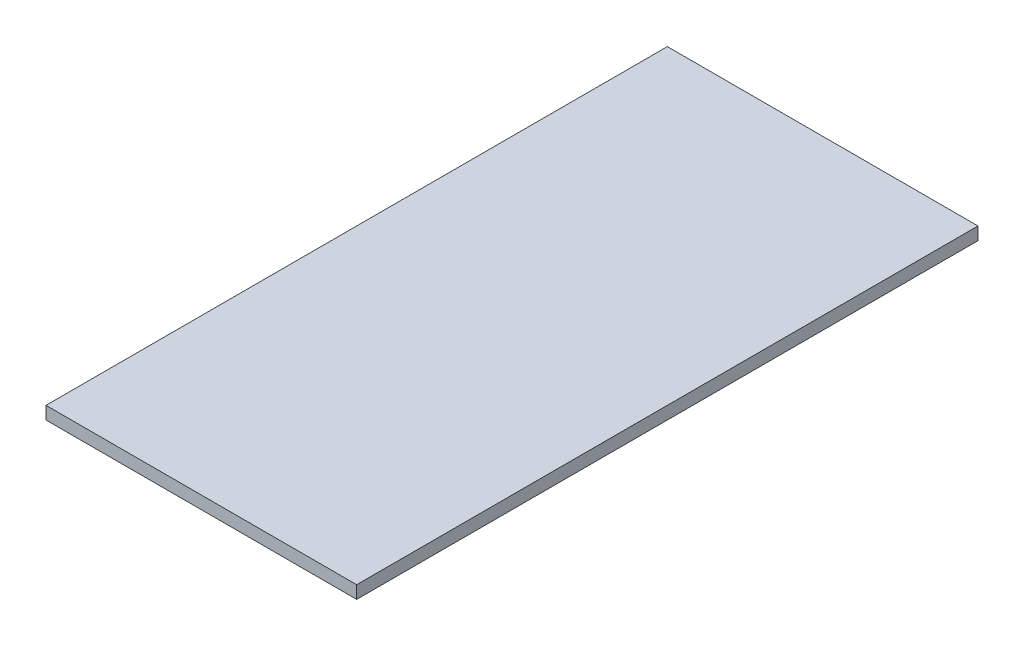
SolidWorks part; units mm, degrees
ref_plane "Front Plane" through (0, 0, 0) normal (0, 0, 1) x (1, 0, 0)
ref_plane "Top Plane" through (0, 0, 0) normal (0, 1, 0) x (1, 0, 0)
ref_plane "Right Plane" through (0, 0, 0) normal (1, 0, 0) x (0, 0, -1)
sketch "Sketch1" plane through (0, 0, 0) normal (0, 1, 0) x (1, 0, 0)
  line L1 (1219.2, -2438.4) -> (-1219.2, -2438.4)
  line L2 (1219.2, -2438.4) -> (1219.2, 2438.4)
  line L3 (1219.2, 2438.4) -> (-1219.2, 2438.4)
  line L4 (-1219.2, -2438.4) -> (-1219.2, 2438.4)
  line L5 (1219.2, -2438.4) -> (-1219.2, 2438.4) construction
  line L6 (1219.2, 2438.4) -> (-1219.2, -2438.4) construction
  point P0 (0, 0)
  dimension "D1" = 4876.8
  dimension "D2" = 2438.4
extrude "Boss-Extrude1" add sketch "Sketch1" along normal blind 100
sketch "Sketch2" plane through (0, 100, 0) normal (0, 1, 0) x (1, 0, 0)
  line L0 (-1219.2, 2438.4) -> (-1219.2, -2438.4) construction
  line L1 (-919.2, -2338.4) -> (-1169.2, -2338.4)
  line L2 (-919.2, -2338.4) -> (-919.2, -2228.4)
  line L3 (-919.2, -2088.4) -> (-1169.2, -2088.4)
  line L4 (-1169.2, -2338.4) -> (-1169.2, -2088.4)
  line L5 (-919.2, -2338.4) -> (-1169.2, -2088.4) construction
  line L6 (-919.2, -2088.4) -> (-1169.2, -2338.4) construction
  line L7 (-1219.2, -2438.4) -> (1219.2, -2438.4) construction
  line L8 (-919.2, -2228.4) -> (-519.2, -2228.4)
  line L9 (-919.2, -2213.4) -> (-874.2776, -2213.4) construction
  line L10 (-919.2, -2198.4) -> (-519.2, -2198.4)
  line L11 (-919.2, -2198.4) -> (-919.2, -2088.4)
  line L12 (518.6973, -2271.9533) -> (948.6973, -2271.9533)
  line L13 (518.6973, -2241.9533) -> (918.6973, -2241.9533)
  line L14 (918.6973, -2241.9533) -> (918.6973, -1841.9533)
  line L15 (948.6973, -2271.9533) -> (948.6973, -1841.9533)
  line L17 (518.6973, -1539.0748) -> (218.6973, -1539.0748)
  line L18 (218.6973, -1539.0748) -> (218.6973, -1567.2032)
  line L19 (218.6973, -1567.2032) -> (518.6973, -1567.2032)
  line L20 (-1019.2, -1938.4) -> (-719.2, -1938.4)
  line L21 (-719.2, -1938.4) -> (-719.2, -1908.4)
  line L22 (-719.2, -1908.4) -> (-989.2, -1908.4)
  line L23 (-989.2, -1908.4) -> (-989.2, -415)
  line L24 (-989.2, -415) -> (-479.8558, -415)
  line L25 (300, -400) -> (-1082.2018, -400) construction
  line L26 (-1019.2, -1938.4) -> (-1019.2, -385)
  line L27 (-1019.2, -385) -> (-479.8558, -385)
  line L28 (300, -400) -> (300, -1150) construction
  line L29 (300, -400) -> (830.3301, -930.3301) construction
  line L30 (819.6179, -940.8301) -> (300, -421.2121)
  line L31 (300, -400) -> (-230.3301, 130.3301) construction
  line L32 (840.8301, -919.6179) -> (321.2121, -400)
  line L33 (300, -400) -> (830.3301, 130.3301) construction
  line L34 (830.3301, 130.3301) -> (-230.3301, -930.3301) construction
  line L35 (-240.8301, -919.6179) -> (278.7879, -400)
  line L36 (840.8301, 119.6179) -> (321.2121, -400)
  line L37 (300, -378.7879) -> (819.6179, 140.8301)
  line L38 (278.7879, -400) -> (-240.8301, 119.6179)
  line L39 (300, -421.2121) -> (-219.6179, -940.8301)
  line L40 (300, -378.7879) -> (-219.6179, 140.8301)
  line L41 (300, -400) -> (300, 350) construction
  line L42 (300, 350) -> (300, 632.1211) construction
  line L43 (285, 379.8558) -> (285, 679.8558)
  line L44 (315, 379.8558) -> (315, 679.8558)
  line L45 (285, 679.8558) -> (315, 679.8558)
  line L47 (283.4854, 707.2433) -> (313.3638, 709.8558)
  line L48 (276.8899, 753.4856) -> (306.3073, 759.3304)
  line L49 (270.3336, 781.5256) -> (299.2927, 789.3304)
  line L50 (255.7416, 825.8982) -> (283.6807, 836.8045)
  line L51 (243.6288, 853.9382) -> (270.7213, 866.8045)
  line L52 (221.3238, 894.9789) -> (246.8572, 910.7139)
  line L53 (202.4819, 923.0189) -> (226.6982, 940.7139)
  line L54 (172.9117, 959.1776) -> (195.0611, 979.4001)
  line L55 (144.8258, 987.2176) -> (165.012, 1009.4001)
  line L57 (104.4289, 1065.1132) -> (81.255, 1046.0708)
  line L58 (77.2262, 1102.6314) -> (51.9232, 1086.5256)
  line L59 (64.2637, 1124.5744) -> (37.9461, 1110.1861)
  line L60 (16.6704, 1155.4) -> (44.5324, 1166.5062)
  line L61 (34.3337, 1195.4) -> (5.6734, 1186.5553)
  line L62 (23.3708, 1240.4268) -> (-6.1476, 1235.1065)
  line L63 (-10.1201, 1262.2983) -> (19.6866, 1265.6449)
  line L64 (-12.6825, 1312.2021) -> (17.3102, 1311.9261)
  line L65 (18.3921, 1337.3888) -> (17.294, 1337.4721)
  line L66 (-12.7, 1337.4721) -> (-12.7, 1508.4)
  line L67 (-12.7, 1508.4) -> (17.294, 1508.4)
  line L68 (17.294, 1508.4) -> (17.294, 1337.4721)
  line L69 (2.297, 1508.4) -> (2.297, 2375.9732) construction
  line L70 (-584.703, 2095.4) -> (-884.703, 2095.4)
  line L71 (-584.703, 2095.4) -> (-584.703, 2125.4)
  line L72 (-584.703, 2125.4) -> (-914.703, 2125.4)
  line L73 (-914.703, 2125.4) -> (-914.703, 1825.4)
  line L75 (-884.703, 1825.4) -> (-884.703, 2095.4)
  line L82 (1219.2, 2438.4) -> (-1219.2, 2438.4) construction
  line L83 (126.2742, 1040.9739) -> (108.6188, 1016.7287)
  line L84 (-914.703, 1795.4) -> (-914.703, 1195.4)
  line L86 (-884.703, 565.4) -> (-884.703, 1165.4)
  line L87 (-884.703, 1825.4) -> (-834.703, 1825.4)
  line L88 (-834.703, 1825.4) -> (-834.703, 1795.4)
  line L89 (-834.703, 1795.4) -> (-884.703, 1795.4)
  line L90 (-884.703, 1195.4) -> (-834.703, 1195.4)
  line L91 (-914.703, 1795.4) -> (-964.703, 1795.4)
  line L92 (-964.703, 1795.4) -> (-964.703, 1825.4)
  line L93 (-964.703, 1825.4) -> (-914.703, 1825.4)
  line L94 (-834.703, 1195.4) -> (-834.703, 1165.4)
  line L95 (-834.703, 1165.4) -> (-884.703, 1165.4)
  line L96 (-899.703, 565.4) -> (-899.703, 505.0509) construction
  line L97 (-914.703, 1165.4) -> (-964.703, 1165.4)
  line L98 (-964.703, 1165.4) -> (-964.703, 1195.4)
  line L99 (-964.703, 1195.4) -> (-914.703, 1195.4)
  line L100 (-884.703, 1195.4) -> (-884.703, 1795.4)
  line L101 (-914.703, 1165.4) -> (-914.703, 565.4)
  line L102 (-884.703, 565.4) -> (-774.703, 565.4)
  line L103 (-774.703, 565.4) -> (-774.703, 315.4)
  line L104 (-774.703, 315.4) -> (-1024.703, 315.4)
  line L105 (-1024.703, 315.4) -> (-1024.703, 565.4)
  line L106 (-1024.703, 565.4) -> (-914.703, 565.4)
  line L107 (17.294, 1337.4721) -> (-12.7, 1337.4721)
  line L108 (17.294, 1311.9263) -> (17.294, 1308.4)
  line L109 (889.297, 565.4) -> (779.297, 565.4)
  line L110 (779.297, 565.4) -> (779.297, 315.4)
  line L111 (779.297, 315.4) -> (1029.297, 315.4)
  line L112 (1029.297, 315.4) -> (1029.297, 565.4)
  line L113 (1029.297, 565.4) -> (919.297, 565.4)
  line L114 (919.297, 1165.4) -> (919.297, 565.4)
  line L115 (919.297, 1165.4) -> (969.297, 1165.4)
  line L116 (969.297, 1165.4) -> (969.297, 1195.4)
  line L117 (969.297, 1195.4) -> (919.297, 1195.4)
  line L118 (919.297, 1795.4) -> (919.297, 1195.4)
  line L119 (919.297, 1795.4) -> (969.297, 1795.4)
  line L120 (969.297, 1795.4) -> (969.297, 1825.4)
  line L121 (969.297, 1825.4) -> (919.297, 1825.4)
  line L122 (919.297, 2125.4) -> (919.297, 1825.4)
  line L123 (589.297, 2125.4) -> (919.297, 2125.4)
  line L124 (589.297, 2095.4) -> (589.297, 2125.4)
  line L125 (589.297, 2095.4) -> (889.297, 2095.4)
  line L126 (889.297, 1825.4) -> (889.297, 2095.4)
  line L127 (889.297, 1825.4) -> (839.297, 1825.4)
  line L128 (839.297, 1825.4) -> (839.297, 1795.4)
  line L129 (839.297, 1795.4) -> (889.297, 1795.4)
  line L130 (889.297, 1195.4) -> (889.297, 1795.4)
  line L131 (889.297, 1195.4) -> (839.297, 1195.4)
  line L132 (839.297, 1195.4) -> (839.297, 1165.4)
  line L133 (839.297, 1165.4) -> (889.297, 1165.4)
  line L134 (889.297, 565.4) -> (889.297, 1165.4)
  arc A0 (-519.2, -2228.4) -> (-256.4254, -2117.5698) centre (-519.2, -1861.47) ccw
  arc A1 (-519.2, -2198.4) -> (-277.9097, -2096.6312) centre (-519.2, -1861.47) ccw
  arc A3 (208.9279, -2130.8016) -> (-256.4254, -2117.5698) centre (-29.8396, -2338.4) ccw
  arc A4 (231.5673, -2111.1176) -> (518.6973, -2241.9533) centre (518.6973, -1861.47) ccw
  arc A5 (208.9279, -2130.8016) -> (518.6973, -2271.9533) centre (518.6973, -1861.47) ccw
  arc A6 (231.5673, -2111.1176) -> (-277.9097, -2096.6312) centre (-29.8396, -2338.4) ccw
  arc A7 (918.6973, -1841.9533) -> (518.6973, -1567.2032) centre (518.6973, -1995.7519) ccw
  arc A8 (948.6973, -1841.9533) -> (518.6973, -1539.0748) centre (518.6973, -1995.7519) ccw
  arc A9 (840.8301, -919.6179) -> (840.8301, 119.6179) centre (300, -400) ccw
  arc A10 (-479.8558, -415) -> (315, 379.8558) centre (300, -400) ccw
  arc A11 (-240.8301, 119.6179) -> (-240.8301, -919.6179) centre (300, -400) ccw
  arc A12 (-219.6179, -940.8301) -> (819.6179, -940.8301) centre (300, -400) ccw
  arc A13 (819.6179, 140.8301) -> (-219.6179, 140.8301) centre (300, -400) ccw
  arc A14 (285, 379.8558) -> (-479.8558, -385) centre (300, -400) ccw
  arc A17 (-12.7, 1308.4) -> (-10.1201, 1262.2983) centre (400.4986, 1308.4) ccw
  arc A18 (17.294, 1308.4) -> (19.6866, 1265.6449) centre (400.4986, 1308.4) ccw
  arc A19 (270.3336, 781.5256) -> (255.7416, 825.8982) centre (-143.9653, 669.8681) ccw
  arc A20 (283.4854, 707.2433) -> (276.8899, 753.4856) centre (-143.9653, 669.8681) ccw
  arc A21 (313.3638, 709.8558) -> (306.3073, 759.3304) centre (-143.9653, 669.8681) ccw
  arc A22 (299.2927, 789.3304) -> (283.6807, 836.8045) centre (-143.9653, 669.8681) ccw
  arc A23 (270.7213, 866.8045) -> (246.8572, 910.7139) centre (-143.9653, 669.8681) ccw
  arc A24 (243.6288, 853.9382) -> (221.3238, 894.9789) centre (-143.9653, 669.8681) ccw
  arc A25 (226.6982, 940.7139) -> (195.0611, 979.4001) centre (-143.9653, 669.8681) ccw
  arc A26 (202.4819, 923.0189) -> (172.9117, 959.1776) centre (-143.9653, 669.8681) ccw
  arc A27 (144.8258, 987.2176) -> (108.6188, 1016.7287) centre (-143.9653, 669.8681) ccw
  arc A28 (165.012, 1009.4001) -> (126.2742, 1040.9739) centre (-143.9653, 669.8681) ccw
  arc A29 (51.9232, 1086.5256) -> (81.255, 1046.0708) centre (400.4986, 1308.4) ccw
  arc A30 (77.2262, 1102.6314) -> (104.4289, 1065.1132) centre (400.4986, 1308.4) ccw
  arc A31 (44.5324, 1166.5062) -> (64.2637, 1124.5744) centre (400.4986, 1308.4) ccw
  arc A32 (16.6704, 1155.4) -> (37.9461, 1110.1861) centre (400.4986, 1308.4) ccw
  arc A33 (23.3708, 1240.4268) -> (34.3337, 1195.4) centre (400.4986, 1308.4) ccw
  arc A34 (-6.1476, 1235.1065) -> (5.6734, 1186.5553) centre (400.4986, 1308.4) ccw
  arc A35 (17.3102, 1311.9261) -> (19.6866, 1265.6449) centre (400.4986, 1308.4) ccw
  arc A36 (-12.6825, 1312.2021) -> (-10.1201, 1262.2983) centre (400.4986, 1308.4) ccw
  arc A38 (77.2262, 1102.6314) -> (104.4289, 1065.1132) centre (400.4986, 1308.4) ccw
  arc A39 (51.9232, 1086.5256) -> (81.255, 1046.0708) centre (400.4986, 1308.4) ccw
  arc A40 (44.5324, 1166.5062) -> (64.2637, 1124.5744) centre (400.4986, 1308.4) ccw
  arc A41 (16.6704, 1155.4) -> (37.9461, 1110.1861) centre (400.4986, 1308.4) ccw
  arc A42 (23.3708, 1240.4268) -> (34.3337, 1195.4) centre (400.4986, 1308.4) ccw
  arc A43 (-6.1476, 1235.1065) -> (5.6734, 1186.5553) centre (400.4986, 1308.4) ccw
  point P0 (-1044.2, -2213.4)
  point P9 (-1044.2, -2338.4)
  dimension "D9" = 673.8601
  dimension "D10" = 733.8601
  dimension "D11" = 632.794
  dimension "D12" = 489.3604
  dimension "D13" = 760.9667
  dimension "D15" = 30
  dimension "D21" = 857.0975
  dimension "D28" = 1500
  dimension "D31" = 1560
  dimension "D1" = 250
  dimension "D2" = 250
  dimension "D3" = 50
  dimension "D4" = 100
  dimension "D5" = 400
  dimension "D6" = 15
  dimension "D7" = 15
  dimension "D8" = 125
  dimension "D14" = 1037.8973
  dimension "D16" = 30
  dimension "D17" = 30
  dimension "D18" = 400
  dimension "D19" = 430
  dimension "D20" = 400
  dimension "D22" = 400
  dimension "D23" = 300
  dimension "D24" = 300
  dimension "D25" = 270
  dimension "D26" = 30
  dimension "D27" = 150
  dimension "D29" = 300
  dimension "D30" = 400
  dimension "D32" = 15
  dimension "D33" = 15
  dimension "D34" = 100
  dimension "D35" = 45
  dimension "D36" = 15
  dimension "D37" = 45
  dimension "D38" = 15
  dimension "D39" = 15
  dimension "D40" = 15
  dimension "D41" = 1499.7
  dimension "D42" = 519.6179
  dimension "D43" = 45
  dimension "D44" = 15
  dimension "D45" = 15
  dimension "D46" = 15
  dimension "D47" = 15
  dimension "D48" = 1499.7
  dimension "D49" = 15
  dimension "D50" = 15
  dimension "D51" = 300
  dimension "D52" = 30
  dimension "D53" = 50
  dimension "D54" = 30
  dimension "D55" = 50
  dimension "D56" = 30
  dimension "D57" = 50
  dimension "D58" = 30
  dimension "D59" = 50
  dimension "D60" = 30
  dimension "D61" = 50
  dimension "D62" = 1206.5
  dimension "D63" = 50
  dimension "D64" = 40
  dimension "D65" = 50
  dimension "D66" = 40
  dimension "D67" = 50
  dimension "D68" = 40
  dimension "D69" = 50
  dimension "D70" = 40
  dimension "D71" = 200
  dimension "D72" = 29.994
  dimension "D73" = 587
  dimension "D74" = 30
  dimension "D75" = 587
  dimension "D76" = 300
  dimension "D77" = 30
  dimension "D78" = 930
  dimension "D79" = 300
  dimension "D80" = 1260
  dimension "D81" = 30
  dimension "D82" = 50
  dimension "D83" = 50
  dimension "D84" = 330
  dimension "D85" = 30
  dimension "D86" = 887
  dimension "D87" = 30
  dimension "D88" = 30
  dimension "D89" = 50
  dimension "D90" = 50
  dimension "D91" = 600
  dimension "D92" = 30
  dimension "D93" = 600
  dimension "D94" = 125
  dimension "D95" = 125
  dimension "D96" = 250
  dimension "D97" = 110
